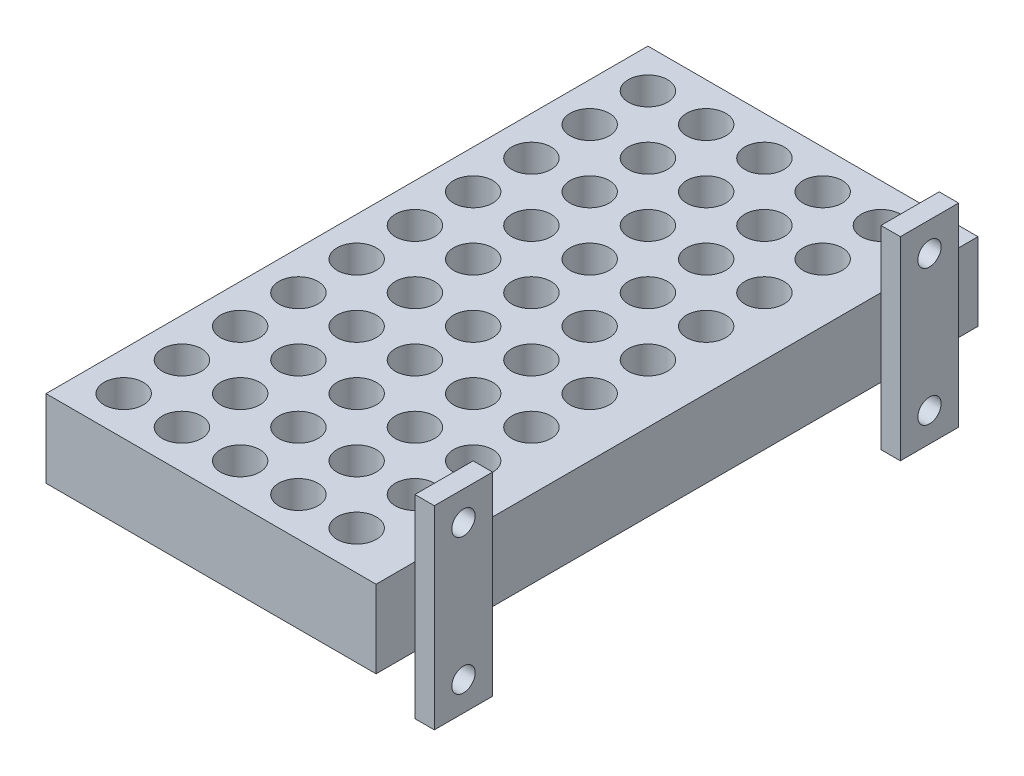
SolidWorks part; units mm, degrees
material "ABS PC"
ref_plane "Front Plane" through (0, 0, 0) normal (0, 0, 1) x (1, 0, 0)
ref_plane "Top Plane" through (0, 0, 0) normal (0, 1, 0) x (1, 0, 0)
ref_plane "Right Plane" through (0, 0, 0) normal (1, 0, 0) x (0, 0, -1)
sketch "Sketch1" plane through (0, 0, 0) normal (0, 1, 0) x (1, 0, 0)
  line L1 (0, 0) -> (85, 0)
  line L2 (0, 0) -> (0, 155)
  line L3 (0, 155) -> (85, 155)
  line L4 (85, 0) -> (85, 155)
  dimension "D1" = 155
  dimension "D2" = 85
extrude "Boss-Extrude1" add sketch "Sketch1" along normal blind 20
sketch "Sketch3" plane through (0, 20, 0) normal (0, 1, 0) x (1, 0, 0)
  line L0 (0, 155) -> (0, 0) construction
  line L1 (85, 155) -> (0, 155) construction
  line L2 (10, 145) -> (25, 145) construction
  line L3 (70, 145) -> (70, 130) construction
  circle A0 centre (10, 145) radius 5.05
  circle A1 centre (25, 145) radius 5.05
  circle A2 centre (40, 145) radius 5.05
  circle A3 centre (55, 145) radius 5.05
  circle A4 centre (70, 145) radius 5.05
  circle A5 centre (70, 130) radius 5.05
  circle A6 centre (55, 130) radius 5.05
  circle A7 centre (40, 130) radius 5.05
  circle A8 centre (25, 130) radius 5.05
  circle A9 centre (10, 130) radius 5.05
  circle A10 centre (70, 115) radius 5.05
  circle A11 centre (55, 115) radius 5.05
  circle A12 centre (40, 115) radius 5.05
  circle A13 centre (25, 115) radius 5.05
  circle A14 centre (10, 115) radius 5.05
  circle A15 centre (70, 100) radius 5.05
  circle A16 centre (55, 100) radius 5.05
  circle A17 centre (40, 100) radius 5.05
  circle A18 centre (25, 100) radius 5.05
  circle A19 centre (10, 100) radius 5.05
  circle A20 centre (70, 85) radius 5.05
  circle A21 centre (55, 85) radius 5.05
  circle A22 centre (40, 85) radius 5.05
  circle A23 centre (25, 85) radius 5.05
  circle A24 centre (10, 85) radius 5.05
  circle A25 centre (70, 70) radius 5.05
  circle A26 centre (55, 70) radius 5.05
  circle A27 centre (40, 70) radius 5.05
  circle A28 centre (25, 70) radius 5.05
  circle A29 centre (10, 70) radius 5.05
  circle A30 centre (70, 55) radius 5.05
  circle A31 centre (55, 55) radius 5.05
  circle A32 centre (40, 55) radius 5.05
  circle A33 centre (25, 55) radius 5.05
  circle A34 centre (10, 55) radius 5.05
  circle A35 centre (70, 40) radius 5.05
  circle A36 centre (55, 40) radius 5.05
  circle A37 centre (40, 40) radius 5.05
  circle A38 centre (25, 40) radius 5.05
  circle A39 centre (10, 40) radius 5.05
  circle A40 centre (70, 25) radius 5.05
  circle A41 centre (55, 25) radius 5.05
  circle A42 centre (40, 25) radius 5.05
  circle A43 centre (25, 25) radius 5.05
  circle A44 centre (10, 25) radius 5.05
  circle A45 centre (70, 10) radius 5.05
  circle A46 centre (55, 10) radius 5.05
  circle A47 centre (40, 10) radius 5.05
  circle A48 centre (25, 10) radius 5.05
  circle A49 centre (10, 10) radius 5.05
  dimension "D1" = 10.1
  dimension "D2" = 10
  dimension "D3" = 10
  dimension "D5" = 15
  dimension "D7" = 15
  dimension "D4" = 5
  dimension "D6" = 10
extrude "Cut-Extrude1" cut sketch "Sketch3" against normal blind 10
sketch "Sketch5" plane through (85, 0, 0) normal (1, 0, 0) x (0, 0, -1)
  line L0 (0, 20) -> (155, 20) construction
  line L1 (10, 35) -> (25, 35)
  line L2 (10, 35) -> (10, -15)
  line L3 (10, -15) -> (25, -15)
  line L4 (25, 35) -> (25, -15)
  line L5 (0, 0) -> (155, 0) construction
  line L6 (0, 20) -> (0, 0) construction
  line L7 (77.5, 60.4226) -> (77.5, -43.5882) construction
  line L9 (155, 20) -> (155, 0) construction
  line L10 (145, -15) -> (130, -15)
  line L11 (145, 35) -> (145, -15)
  line L12 (145, 35) -> (130, 35)
  line L13 (130, 35) -> (130, -15)
  dimension "D1" = 15
  dimension "D2" = 15
  dimension "D3" = 10
  dimension "D4" = 77.5
  dimension "D5" = 15
extrude "Boss-Extrude2" add sketch "Sketch5" along normal blind 5
sketch "Sketch6" plane through (90, 0, 0) normal (1, 0, 0) x (0, 0, -1)
  line L0 (25, 35) -> (10, 35) construction
  line L1 (145, 35) -> (130, 35) construction
  line L2 (130, -15) -> (145, -15) construction
  line L3 (10, -15) -> (25, -15) construction
  line L4 (25, -15) -> (25, 35) construction
  line L5 (10, 35) -> (10, -15) construction
  line L6 (145, -15) -> (145, 35) construction
  circle A0 centre (17.5, 27.5) radius 3
  circle A1 centre (17.5, -7.5) radius 3
  circle A2 centre (137.5, -7.5) radius 3
  circle A3 centre (137.5, 27.5) radius 3
  dimension "D1" = 6
  dimension "D2" = 6
  dimension "D3" = 6
  dimension "D4" = 6
  dimension "D5" = 7.5
  dimension "D7" = 7.5
  dimension "D8" = 7.5
  dimension "D9" = 7.5
  dimension "D10" = 7.5
  dimension "D11" = 7.5
  dimension "D12" = 7.5
  dimension "D6" = 7.5
extrude "Cut-Extrude2" cut sketch "Sketch6" against normal blind 5
